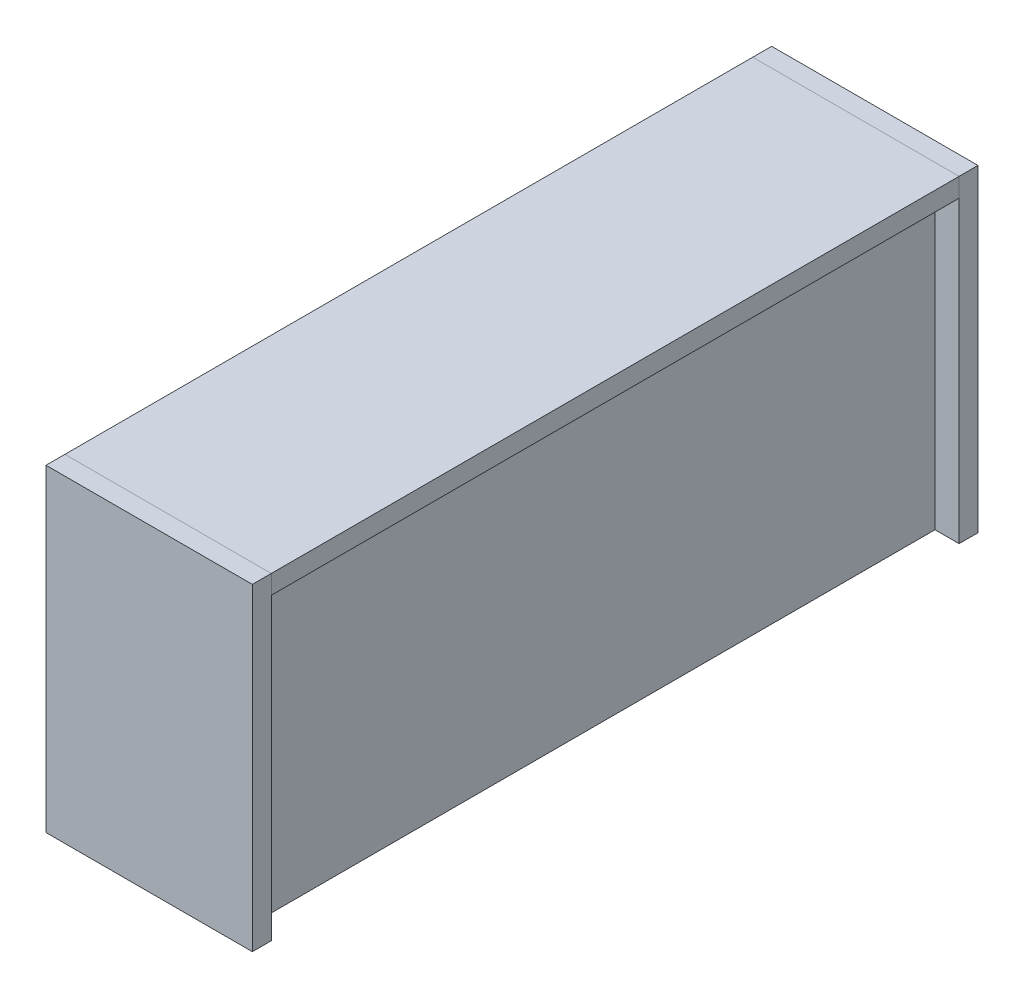
SolidWorks part; units mm, degrees
material "Kiefer"
ref_plane "Ebene vorne" through (0, 0, 0) normal (0, 0, 1) x (1, 0, 0)
ref_plane "Ebene oben" through (0, 0, 0) normal (0, 1, 0) x (1, 0, 0)
ref_plane "Ebene rechts" through (0, 0, 0) normal (1, 0, 0) x (0, 0, -1)
sketch "Skizze1" plane through (0, 0, 0) normal (0, 0, 1) x (1, 0, 0)
  line L0 (0, 0) -> (0, -426.6158) construction
  line L2 (-120, 0) -> (120, 0)
  line L3 (-120, 0) -> (-120, -370)
  line L4 (-120, -370) -> (120, -370)
  line L5 (120, 0) -> (120, -370)
  point P7 (0, -426.6158)
  dimension "D1" = 240
  dimension "D2" = 370
extrude "Aufsatz-Linear austragen1" add sketch "Skizze1" along normal blind 22
sketch "Skizze2" plane through (0, 0, 22) normal (0, 0, 1) x (1, 0, 0)
  line L0 (0, 0) -> (0, -419.2704) construction
  line L1 (-120, -370) -> (120, -370) construction
  line L2 (70, -22) -> (92, -22)
  line L3 (70, -22) -> (70, -370)
  line L4 (70, -370) -> (92, -370)
  line L5 (92, -22) -> (92, -370)
  line L6 (-70, -22) -> (-92, -22)
  line L7 (-70, -22) -> (-70, -370)
  line L8 (-70, -370) -> (-92, -370)
  line L9 (-92, -22) -> (-92, -370)
  line L10 (120, 0) -> (-120, 0) construction
  dimension "D1" = 22
  dimension "D2" = 140
  dimension "D3" = 22
extrude "Aufsatz-Linear austragen2" add sketch "Skizze2" along normal blind 800 separate body
sketch "Skizze3" plane through (0, 0, 22) normal (0, 0, 1) x (1, 0, 0)
  line L0 (120, -370) -> (120, 0) construction
  line L1 (-120, 0) -> (120, 0)
  line L2 (-120, 0) -> (-120, -22)
  line L3 (-120, -22) -> (120, -22)
  line L4 (120, 0) -> (120, -22)
  line L5 (92, -22) -> (70, -22) construction
extrude "Aufsatz-Linear austragen3" add sketch "Skizze3" along normal up to surface (800 mm away) separate body up to face at (81, -196, 822)
sketch "Skizze4" plane through (0, 0, 822) normal (0, 0, 1) x (1, 0, 0)
  line L1 (-120, 0) -> (120, 0)
  line L2 (-120, 0) -> (-120, -370)
  line L3 (-120, -370) -> (120, -370)
  line L4 (120, 0) -> (120, -370)
extrude "Aufsatz-Linear austragen4" add sketch "Skizze4" along normal blind 22 separate body
